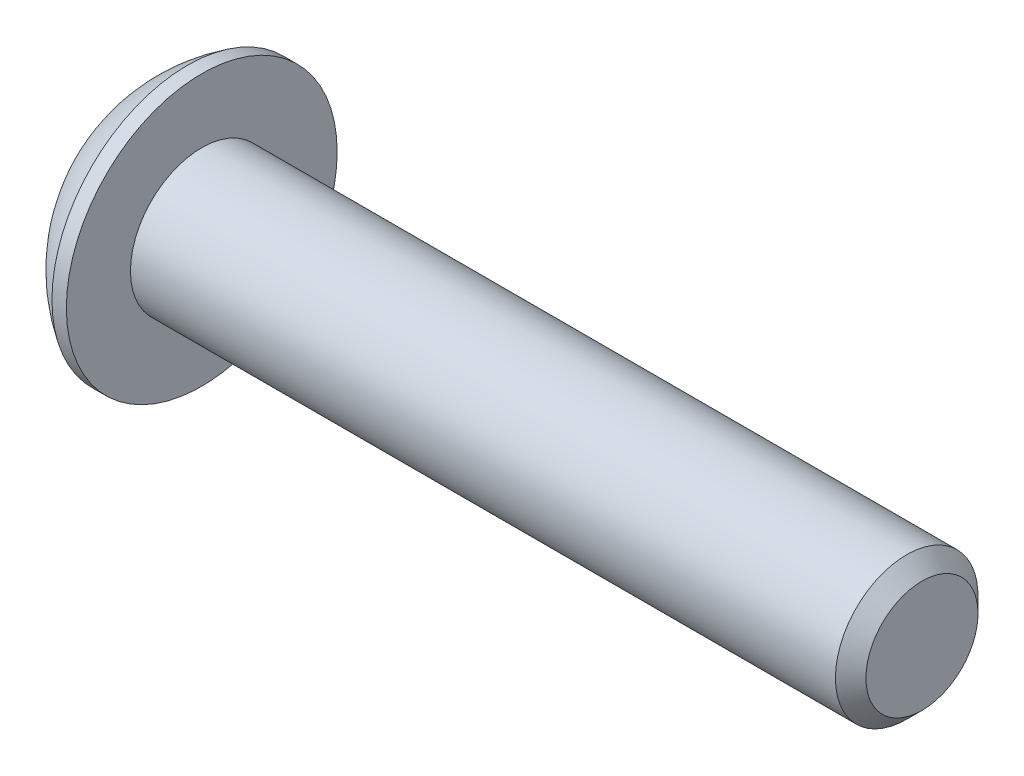
SolidWorks part; units mm, degrees
ref_plane "Plane1" through (0, 0, 0) normal (0, 0, 1) x (1, 0, 0)
ref_plane "Plane2" through (0, 0, 0) normal (0, 1, 0) x (1, 0, 0)
ref_plane "Plane3" through (0, 0, 0) normal (1, 0, 0) x (0, 0, -1)
sketch "BodySke" plane through (0, 0, 0) normal (0, 0, 1) x (1, 0, 0)
  line L0 (14.0208, 0) -> (14.0208, 0.9881)
  line L1 (13.7516, 1.2573) -> (1.3208, 1.2573)
  line L2 (1.3208, 1.2573) -> (1.3208, 2.3876)
  line L3 (1.3208, 2.3876) -> (1.0668, 2.3876)
  line L4 (0, 0) -> (101.6, 0) construction
  line L5 (1.3208, -2.3876) -> (1.0668, -2.3876) construction
  line L6 (55.6768, -1.2573) -> (1.3208, -1.2573) construction
  line L7 (14.0208, 0) -> (0, 0)
  line L8 (0, 1.1938) -> (0, -1.1938) construction
  line L9 (0, 0) -> (0, 1.1938)
  line L10 (14.0208, 0.9881) -> (13.7516, 1.2573)
  line L11 (14.0208, -0.9881) -> (13.7516, -1.2573) construction
  line L12 (1.7755, 9.525) -> (1.7755, -1.2573) construction
  line L13 (1.3208, 9.525) -> (1.3208, -1.2573) construction
  arc A1 (0, 1.1938) -> (1.0668, 2.3876) centre (2.5373, 0) cw
  dimension "Diameter" = 2.5146
  dimension "Length" = 12.7
  dimension "Head_dia" = 4.7752
  dimension "D1" = 2.3876
  dimension "Head_ht" = 1.3208
  dimension "Head_side_ht" = 0.254
  dimension "Minor_dia" = 1.9761
  dimension "Body_ch_ang" = 45
  dimension "Advance" = 0.4547
  dimension "Thread_nom" = 12.7
revolve "BaseBody" add sketch "BodySke" angle 360 about L4
cosmetic thread "ThreadCosmetic" parameters "Thread_length"=12.2453, "Thread_minor"=1.9761
sketch "Sketch2" plane through (0, 0, 0) normal (0, 0, 1) x (1, 0, 0)
  line L0 (0, 0.7874) -> (0.889, 0.7874)
  line L1 (0.889, 0.7874) -> (1.3436, 0)
  line L3 (1.3436, 0) -> (0, 0)
  line L4 (0, 0) -> (0, 0.7874)
  line L5 (0, -0.7874) -> (0.889, -0.7874) construction
  line L6 (0, 0) -> (47.625, 0) construction
  dimension "D2" = 60
  dimension "PreBroach_depth" = 0.889
  dimension "PreBroach_dia" = 1.5748
revolve "PreBroach" cut sketch "Sketch2" angle 360 about L6
sketch "Sketch3" plane through (0, 0, 0) normal (1, 0, 0) x (0, 0, -1)
  line L0 (-0.7874, -0.4546) -> (-0.7874, 0.4546)
  line L1 (-0.7874, 0.4546) -> (0, 0.9092)
  line L2 (0, 0.9092) -> (0.7874, 0.4546)
  line L3 (0.7874, 0.4546) -> (0.7874, -0.4546)
  line L4 (0.7874, -0.4546) -> (0, -0.9092)
  line L5 (0, -0.9092) -> (-0.7874, -0.4546)
  dimension "Hex_size" = 1.5748
  dimension "D3" = 1.5748
  dimension "D1" = 0.7874
  dimension "D2" = 0.7874
extrude "Hex" cut sketch "Sketch3" along normal blind 0.889
sketch "Sketch4" plane through (0, 9.525, 0) normal (1, 0, 0) x (0, 0, -1)
  line L0 (0, -9.525) -> (0.9398, -9.525)
  line L1 (0, -9.525) -> (6.1484, -5.9752) construction
  line L2 (0, -9.525) -> (0.4699, -8.7111)
  line L3 (0.7832, -9.3075) -> (0.8962, -9.2422)
  line L4 (0.58, -8.9555) -> (0.693, -8.8902)
  arc A0 (0.7832, -9.3075) -> (0.58, -8.9555) centre (0, -9.525) ccw
  arc A1 (0.9398, -9.525) -> (0.8962, -9.2422) centre (0, -9.525) ccw
  arc A2 (0.4699, -8.7111) -> (0.693, -8.8902) centre (0, -9.525) cw
  dimension "Spline_n_dim" = 1.6256
  dimension "Spline_m_dim" = 1.8796
  dimension "D1" = 30
  dimension "D2" = 60
  dimension "Spline_p_dim" = 0.4064
  dimension "D3" = 0.2032
extrude "Spline" [suppressed] cut sketch "Sketch4" along normal blind 0.889
pattern_circular "CirPattern1" [suppressed] count 6 every 60 about axis through (0, 0, 0) along (1, 0, 0)
sketch "ThdSchSke" plane through (0, 0, 0) normal (0, 0, 1) x (1, 0, 0)
  line L0 (1.7755, -0.9881) -> (1.5869, -1.2573)
  line L1 (1.7755, -0.9881) -> (1.964, -1.2573)
  line L2 (1.964, -1.2573) -> (1.964, -1.5716)
  line L3 (-3.175, 0) -> (5.1513, 0) construction
  line L5 (1.964, -1.5716) -> (1.5869, -1.5716)
  line L6 (1.5869, -1.5716) -> (1.5869, -1.2573)
  dimension "Diameter" = 2.5146
  dimension "Thread_minor" = 1.9761
  dimension "SideAngle" = 55
  dimension "VeeAngle" = 70
  dimension "Overcut" = 3.1432
  dimension "Start" = 1.7755
revolve "ThreadSchematic" [suppressed] cut sketch "ThdSchSke" angle 360 about L3
pattern_linear "ThdSchPat" [suppressed]
equation "\"D1@BodySke\" = \"Head_dia@BodySke\" * .5"
equation "\"Thread_minor@ThreadCosmetic\" = \"Minor_dia@BodySke\""
equation "\"D1@Sketch3\" = \"Hex_size@Sketch3\" / 2"
equation "\"D2@Sketch3\" = \"D1@Sketch3\""
equation "\"D3@Sketch3\" = \"Hex_size@Sketch3\""
equation "\"D3@Sketch4\" = \"Spline_p_dim@Sketch4\" / 2"
equation "\"D1@Sketch4\" = \"D2@Sketch4\" / 2"
equation "\"Thread_length@ThreadCosmetic\" = ((sgn( (\"Length@BodySke\" - \"Advance@BodySke\" ) - \"Thread_nom@BodySke\" )-1)*( (\"Length@BodySke\" - \"Advance@BodySke\" ) - \"Thread_nom@BodySke\" ))/-2+ \"Thread_nom@BodySke\""
equation "\"Thread_minor@ThdSchSke\" = \"Minor_dia@BodySke\""
equation "\"Diameter@ThdSchSke\" = \"Diameter@BodySke\""
equation "\"Overcut@ThdSchSke\" = \"Diameter@BodySke\" * 1.25"
equation "\"Start@ThdSchSke\" = \"Head_ht@BodySke\" + \"Length@BodySke\" - \"Thread_length@ThreadCosmetic\"  '---Non-countersunk---"
equation "\"Num_threads@ThdSchPat\" = int( \"Thread_length@ThreadCosmetic\" / \"Advance@BodySke\" + 0.999 )  + 1"
equation "\"Advance@ThdSchPat\" = \"Thread_length@ThreadCosmetic\" /  (\"Num_threads@ThdSchPat\" - 1) 'relax it"
equation "\"Num_threads@ThdSchPat\" = \"Num_threads@ThdSchPat\" - sgn( \"Num_threads@ThdSchPat\" - 1) '---chamfered tips only---"
